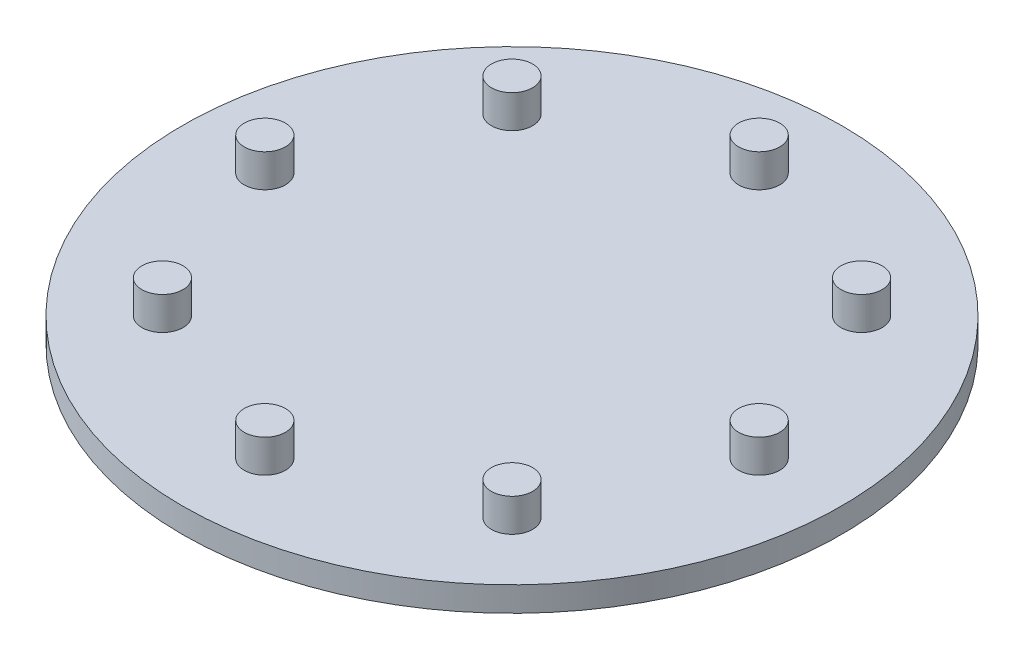
SolidWorks part; units mm, degrees
ref_plane "Front Plane" through (0, 0, 0) normal (0, 0, 1) x (1, 0, 0)
ref_plane "Top Plane" through (0, 0, 0) normal (0, 1, 0) x (1, 0, 0)
ref_plane "Right Plane" through (0, 0, 0) normal (1, 0, 0) x (0, 0, -1)
sketch "Sketch1" plane through (0, 0, 0) normal (0, 1, 0) x (1, 0, 0)
  circle A0 centre (0, 0) radius 40
  dimension "D1" = 80
extrude "Boss-Extrude1" add sketch "Sketch1" along normal blind 3
sketch "Sketch2" plane through (0, 3, 0) normal (0, 1, 0) x (1, 0, 0)
  circle A0 centre (0, 30) radius 2.5
  circle A1 centre (21.2132, 21.2132) radius 2.5
  circle A2 centre (30, 0) radius 2.5
  circle A3 centre (21.2132, -21.2132) radius 2.5
  circle A4 centre (0, -30) radius 2.5
  circle A5 centre (-21.2132, -21.2132) radius 2.5
  circle A6 centre (-30, 0) radius 2.5
  circle A7 centre (-21.2132, 21.2132) radius 2.5
  point P19 (0, 0)
  dimension "D1" = 5
  dimension "D2" = 30
  dimension "D3" = 8
extrude "Boss-Extrude2" add sketch "Sketch2" along normal blind 4
